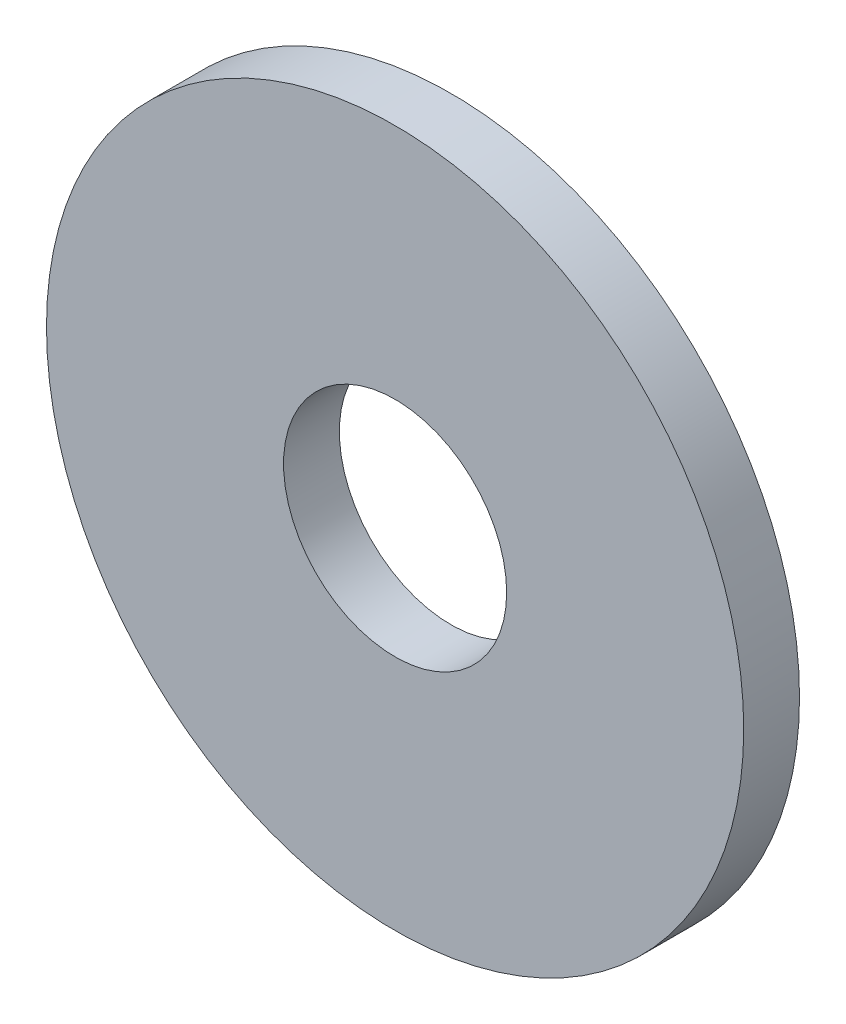
SolidWorks part; units mm, degrees
ref_plane "Front Plane" through (0, 0, 0) normal (0, 0, 1) x (1, 0, 0)
ref_plane "Top Plane" through (0, 0, 0) normal (0, 1, 0) x (1, 0, 0)
ref_plane "Right Plane" through (0, 0, 0) normal (1, 0, 0) x (0, 0, -1)
sketch "S01 - Wide washer for pin retention" plane through (0, 0, 0) normal (0, 0, 1) x (1, 0, 0)
  circle A0 centre (0, 0) radius 5
  circle A1 centre (0, 0) radius 1.6
extrude "01 - Wide washer for pin retention" add sketch "S01 - Wide washer for pin retention" along normal blind 0.8
